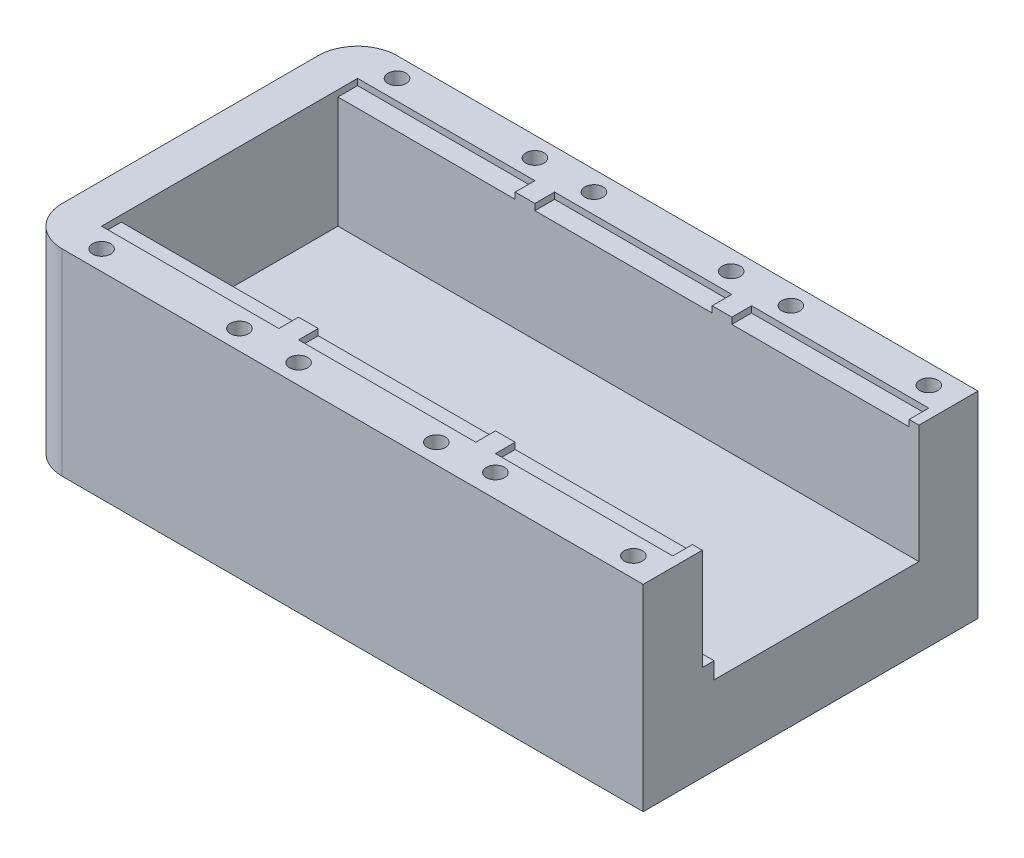
SolidWorks part; units mm, degrees
ref_plane "Ebene vorne" through (0, 0, 0) normal (0, 0, 1) x (1, 0, 0)
ref_plane "Ebene oben" through (0, 0, 0) normal (0, 1, 0) x (1, 0, 0)
ref_plane "Ebene rechts" through (0, 0, 0) normal (1, 0, 0) x (0, 0, -1)
sketch "Skizze2" plane through (0, 0, 0) normal (0, 0, 1) x (1, 0, 0)
  line L1 (0, 0) -> (315, 0)
  line L2 (0, 0) -> (0, 50)
  line L3 (0, 50) -> (315, 50)
  line L4 (315, 0) -> (315, 50)
  dimension "D1" = 315
  dimension "D2" = 50
extrude "Aufsatz-Linear austragen1" add sketch "Skizze2" along normal blind 85
sketch "Skizze4" plane through (0, 50, 0) normal (0, 1, 0) x (1, 0, 0)
  line L0 (315, 0) -> (0, 0) construction
  line L1 (10, -15) -> (305, -15)
  line L2 (10, -15) -> (10, -70)
  line L3 (10, -70) -> (305, -70)
  line L4 (305, -15) -> (305, -70)
  line L5 (315, -85) -> (0, -85) construction
  line L6 (0, -85) -> (0, 0) construction
  line L7 (315, -85) -> (315, 0) construction
  dimension "D1" = 15
  dimension "D2" = 15
  dimension "D3" = 10
  dimension "D4" = 10
extrude "Schnitt-Linear austragen1" cut sketch "Skizze4" against normal blind 30
fillet "Verrundung1" radius 10 1 edges at (315, 25, 0)
fillet "Verrundung2" radius 10 1 edges at (315, 25, 85)
fillet "Verrundung3" radius 10 1 edges at (0, 25, 85)
fillet "Verrundung4" radius 10 1 edges at (0, 25, 0)
sketch "Skizze11" plane through (0, 50, 0) normal (0, 1, 0) x (1, 0, 0)
  line L0 (10, -70) -> (305, -70) construction
  line L1 (10, -15) -> (55, -15)
  line L2 (10, -15) -> (10, -10)
  line L3 (10, -10) -> (55, -10)
  line L4 (55, -15) -> (55, -10)
  line L5 (55, -70) -> (10, -70)
  line L6 (55, -70) -> (55, -75)
  line L7 (55, -75) -> (10, -75)
  line L8 (10, -70) -> (10, -75)
  line L9 (305, -15) -> (10, -15) construction
  line L10 (60, -75) -> (105, -75)
  line L11 (60, -75) -> (60, -70)
  line L12 (60, -70) -> (105, -70)
  line L13 (105, -75) -> (105, -70)
  line L14 (110, -75.0087) -> (155, -75.0087)
  line L15 (110, -75.0087) -> (110, -70)
  line L16 (110, -70) -> (155, -70)
  line L17 (155, -75.0087) -> (155, -70)
  line L18 (160, -75.0087) -> (205, -75.0087)
  line L19 (160, -75.0087) -> (160, -70)
  line L20 (160, -70) -> (205, -70)
  line L21 (205, -75.0087) -> (205, -70)
  line L22 (210, -75) -> (255, -75)
  line L23 (210, -75) -> (210, -70)
  line L24 (210, -70) -> (255, -70)
  line L25 (255, -75) -> (255, -70)
  line L26 (260, -75) -> (305, -75)
  line L27 (260, -75) -> (260, -70)
  line L28 (260, -70) -> (305, -70)
  line L29 (305, -75) -> (305, -70)
  line L30 (305, -15) -> (260, -15)
  line L31 (305, -15) -> (305, -10)
  line L32 (305, -10) -> (260, -10)
  line L33 (260, -15) -> (260, -10)
  line L35 (255, -15) -> (210, -15)
  line L36 (255, -15) -> (255, -10)
  line L37 (255, -10) -> (210, -10)
  line L38 (210, -15) -> (210, -10)
  line L39 (205, -15) -> (160, -15)
  line L40 (205, -15) -> (205, -10)
  line L41 (205, -10) -> (160, -10)
  line L42 (160, -15) -> (160, -10)
  line L43 (155, -15) -> (110, -15)
  line L44 (155, -15) -> (155, -10)
  line L45 (155, -10) -> (110, -10)
  line L46 (110, -15) -> (110, -10)
  line L47 (105, -15) -> (60, -15)
  line L48 (105, -15) -> (105, -10)
  line L49 (105, -10) -> (60, -10)
  line L50 (60, -15) -> (60, -10)
  dimension "D1" = 45
  dimension "D2" = 5
  dimension "D3" = 45
  dimension "D4" = 5
  dimension "D5" = 5
  dimension "D6" = 5
  dimension "D7" = 5
  dimension "D8" = 5
  dimension "D9" = 5
  dimension "D10" = 45
  dimension "D11" = 45
  dimension "D12" = 45
  dimension "D13" = 45
  dimension "D14" = 45
  dimension "D15" = 5
  dimension "D16" = 5
  dimension "D17" = 5
  dimension "D18" = 5
  dimension "D19" = 45
  dimension "D20" = 45
  dimension "D21" = 45
  dimension "D22" = 45
  dimension "D23" = 5
  dimension "D24" = 5
  dimension "D25" = 5
  dimension "D26" = 5
  dimension "D27" = 5
  dimension "D28" = 5
  dimension "D29" = 5
  dimension "D30" = 5
extrude "Schnitt-Linear austragen4" cut sketch "Skizze11" against normal blind 1.6
sketch "Skizze13" plane through (0, 20, 0) normal (0, 1, 0) x (1, 0, 0)
  line L0 (10, -15) -> (10, -70) construction
  line L1 (305, -70) -> (10, -70)
  line L2 (305, -70) -> (305, -67)
  line L3 (305, -67) -> (10, -67)
  line L4 (10, -70) -> (10, -67)
  line L5 (305, -15) -> (10, -15) construction
  dimension "D1" = 52
extrude "Aufsatz-Linear austragen2" add sketch "Skizze13" along normal blind 4.2
sketch "Skizze14" plane through (305, 0, 0) normal (-1, 0, 0) x (0, 0, 1)
  line L0 (15, 20) -> (15, 48.4) construction
  line L1 (31, 26.4) -> (39, 26.4)
  line L2 (31, 26.4) -> (31, 22.4)
  line L3 (31, 22.4) -> (39, 22.4)
  line L4 (39, 26.4) -> (39, 22.4)
  line L5 (67, 20) -> (15, 20) construction
  dimension "D1" = 8
  dimension "D2" = 4
  dimension "D3" = 16
  dimension "D4" = 2.4
extrude "Schnitt-Linear austragen5" cut sketch "Skizze14" against normal blind 19
sketch "Skizze15" plane through (0, 0, 15) normal (0, 0, 1) x (1, 0, 0)
  line L0 (305, 20) -> (305, 48.4) construction
  line L1 (305, 22.7) -> (255, 22.7)
  line L2 (305, 22.7) -> (305, 24.2)
  line L3 (305, 24.2) -> (255, 24.2)
  line L4 (255, 22.7) -> (255, 24.2)
  line L5 (305, 20) -> (10, 20) construction
  dimension "D1" = 50
  dimension "D2" = 1.5
  dimension "D3" = 2.7
extrude "Aufsatz-Linear austragen3" add sketch "Skizze15" along normal blind 2
sketch "Skizze16" plane through (0, 0, 67) normal (0, 0, -1) x (-1, 0, 0)
  line L1 (-305, 24.2) -> (-255, 24.2)
  line L2 (-305, 24.2) -> (-305, 22.7)
  line L3 (-305, 22.7) -> (-255, 22.7)
  line L4 (-255, 24.2) -> (-255, 22.7)
  dimension "D1" = 50
  dimension "D2" = 1.5
extrude "Aufsatz-Linear austragen4" add sketch "Skizze16" along normal blind 2
sketch "Skizze17" plane through (0, 50, 0) normal (0, 1, 0) x (1, 0, 0)
  line L0 (55, -75) -> (55, -70) construction
  line L1 (305, 0) -> (10, 0) construction
  line L2 (305, -85) -> (10, -85) construction
  line L3 (10, -70) -> (10, -75) construction
  line L4 (10, -10) -> (10, -75) construction
  line L5 (55, -15) -> (55, -10) construction
  line L6 (60, -70) -> (60, -75) construction
  line L7 (105, -75) -> (105, -70) construction
  line L8 (155, -75.0087) -> (155, -70) construction
  line L10 (160, -70) -> (160, -75.0087) construction
  line L11 (205, -75.0087) -> (205, -70) construction
  line L12 (305, -75) -> (305, -10) construction
  line L13 (260, -70) -> (260, -75) construction
  line L14 (255, -75) -> (255, -70) construction
  line L15 (210, -70) -> (210, -75) construction
  line L16 (60, -10) -> (60, -15) construction
  line L18 (110, -10) -> (110, -15) construction
  circle A0 centre (50, -80) radius 2.3
  circle A1 centre (15, -80) radius 2.3
  circle A2 centre (15, -5) radius 2.3
  circle A3 centre (50, -5) radius 2.3
  circle A4 centre (65, -5) radius 2.3
  circle A5 centre (99.8349, -5) radius 2.3
  circle A6 centre (65, -80) radius 2.3
  circle A7 centre (100, -80) radius 2.3
  circle A8 centre (114.1455, -79.164) radius 2.3
  circle A9 centre (150, -80) radius 2.3
  circle A10 centre (165, -80) radius 2.3
  circle A11 centre (200, -80) radius 2.3
  circle A12 centre (215, -80) radius 2.3
  circle A13 centre (250, -80) radius 2.3
  circle A14 centre (265, -80) radius 2.3
  circle A15 centre (300, -80) radius 2.3
  circle A16 centre (300, -5) radius 2.3
  circle A17 centre (265, -5) radius 2.3
  circle A18 centre (250, -5) radius 2.3
  circle A19 centre (215, -5) radius 2.3
  circle A20 centre (200, -5) radius 2.3
  circle A21 centre (165, -5) radius 2.3
  circle A22 centre (150, -5) radius 2.3
  circle A23 centre (115, -5) radius 2.3
  dimension "D1" = 4.6
  dimension "D2" = 4.6
  dimension "D3" = 4.6
  dimension "D4" = 4.6
  dimension "D5" = 5
  dimension "D6" = 5
  dimension "D7" = 5
  dimension "D8" = 5
  dimension "D10" = 5
  dimension "D11" = 5
  dimension "D12" = 5
  dimension "D13" = 4.6
  dimension "D14" = 4.6
  dimension "D15" = 4.6
  dimension "D16" = 4.6
  dimension "D17" = 4.6
  dimension "D18" = 4.6
  dimension "D19" = 4.6
  dimension "D20" = 4.6
  dimension "D21" = 4.6
  dimension "D22" = 4.6
  dimension "D23" = 5
  dimension "D25" = 5
  dimension "D26" = 5
  dimension "D27" = 5
  dimension "D28" = 5
  dimension "D29" = 5
  dimension "D30" = 5
  dimension "D31" = 5
  dimension "D32" = 5
  dimension "D33" = 5
  dimension "D34" = 5
  dimension "D35" = 5
  dimension "D36" = 5
  dimension "D37" = 5
  dimension "D38" = 5
  dimension "D39" = 5
  dimension "D40" = 5
  dimension "D41" = 5
  dimension "D42" = 5
  dimension "D43" = 4.6
  dimension "D44" = 4.6
  dimension "D45" = 4.6
  dimension "D46" = 4.6
  dimension "D47" = 4.6
  dimension "D48" = 4.6
  dimension "D49" = 4.6
  dimension "D50" = 4.6
  dimension "D51" = 4.6
  dimension "D52" = 4.6
  dimension "D53" = 5
  dimension "D54" = 5
  dimension "D9" = 5
  dimension "D24" = 5
extrude "Schnitt-Linear austragen6" cut sketch "Skizze17" against normal blind 4
sketch "Skizze19" plane through (0, 50, 0) normal (0, 1, 0) x (1, 0, 0)
  line L0 (305, -85) -> (10, -85) construction
  line L1 (157.5, -85) -> (340.3, -85)
  line L2 (157.5, -85) -> (157.5, 0)
  line L3 (157.5, 0) -> (340.3, 0)
  line L4 (340.3, -85) -> (340.3, 0)
extrude "Schnitt-Linear austragen8" cut sketch "Skizze19" against normal blind 80
